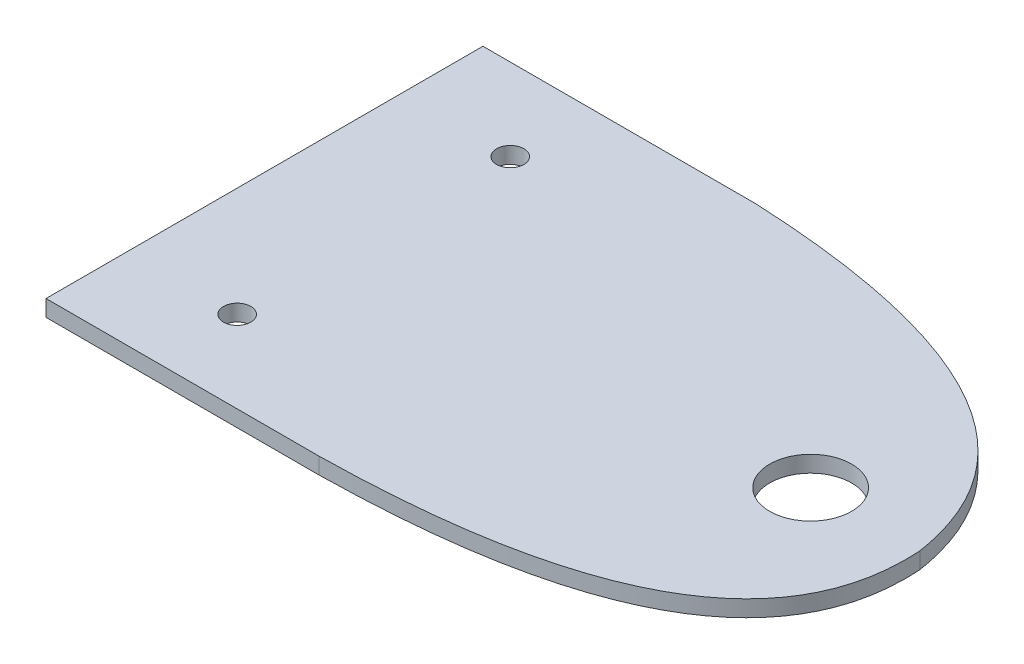
SolidWorks part; units mm, degrees
material "ABS"
ref_plane "Front Plane" through (0, 0, 0) normal (0, 0, 1) x (1, 0, 0)
ref_plane "Top Plane" through (0, 0, 0) normal (0, 1, 0) x (1, 0, 0)
ref_plane "Right Plane" through (0, 0, 0) normal (1, 0, 0) x (0, 0, -1)
sketch "Sketch1" plane through (0, 0, 0) normal (0, 1, 0) x (1, 0, 0)
  line L0 (-100, -40) -> (-50, -40)
  line L1 (-100, -40) -> (-100, 40)
  line L3 (-100, 40) -> (-50, 40)
  arc A0 (20, 0) -> (16.6651, 11.0578) centre (0, 0) ccw
  circle A1 centre (0, 0) radius 7.5
  circle A2 centre (-80, 25) radius 2.5
  circle A3 centre (-80, -25) radius 2.5
  spline S0 degree 2 poles (-50, 40) (14.3899, 37.0556) (20, 0) knots 0 0 0 0.839711 0.839711 0.839711
  spline S1 degree 2 poles (-50, -40) (27.1173, -38.7787) (19.3909, 4.8983) knots 0 0 0 1 1 1
  point P4 (-50, 0)
  dimension "D1" = 15
  dimension "D6" = 15
  dimension "D2" = 80
  dimension "D3" = 20
  dimension "D4" = 15
  dimension "D5" = 20
extrude "Boss-Extrude1" add sketch "Sketch1" along normal blind 3 contours L0 S1 S0 L3 L1 A1
